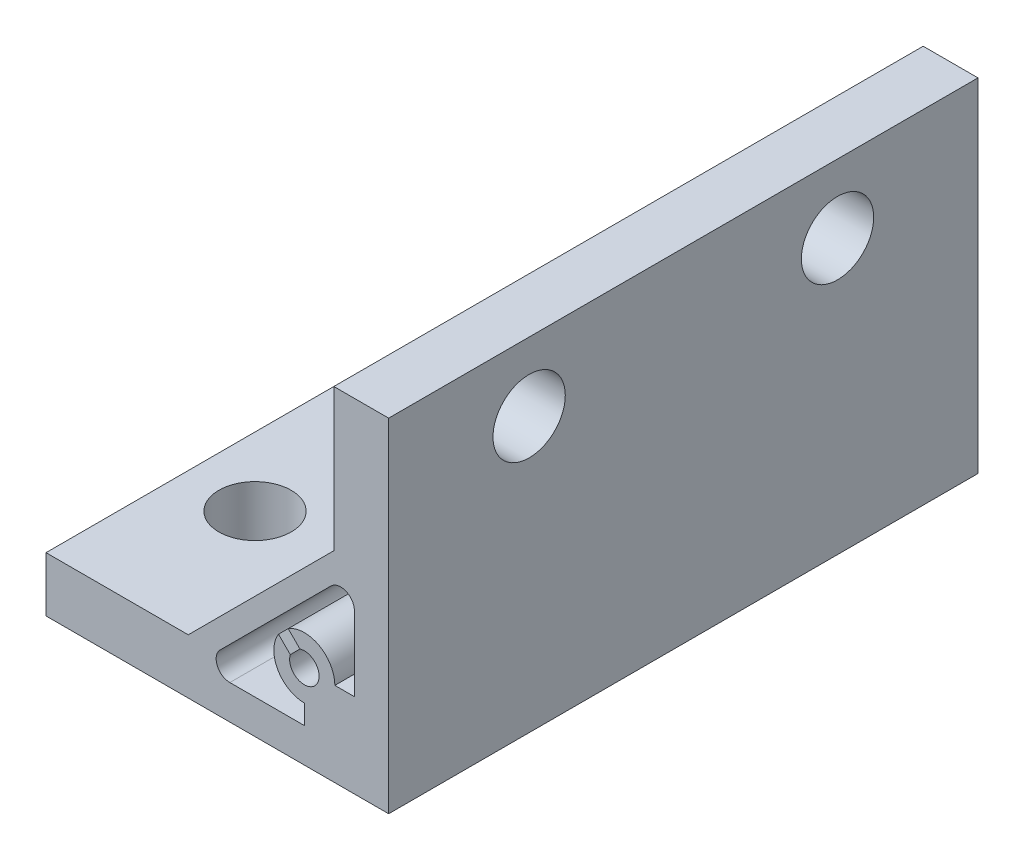
SolidWorks part; units mm, degrees
ref_plane "前视基准面" through (0, 0, 0) normal (0, 0, 1) x (1, 0, 0)
ref_plane "上视基准面" through (0, 0, 0) normal (0, 1, 0) x (1, 0, 0)
ref_plane "右视基准面" through (0, 0, 0) normal (1, 0, 0) x (0, 0, -1)
sketch "草图1" plane through (0, 0, 0) normal (0, 0, 1) x (1, 0, 0)
  line B0 (0, 0) -> (50, 0)
  line B1 (50, 0) -> (50, 50)
  line B2 (0, 8) -> (20.7574, 8)
  line B3 (42, 29.2426) -> (42, 50)
  line B4 (0, 8) -> (0, 0)
  line B5 (42, 50) -> (50, 50)
  line B6 (37.0613, 14.3529) -> (35.341, 16.0733)
  line B7 (35.6471, 12.9387) -> (33.9267, 14.659)
  line B8 (25.4142, 8.4142) -> (41.5858, 24.5858)
  line B9 (20.7574, 8) -> (42, 29.2426)
  line B10 (26.8284, 5) -> (37.7, 5)
  line B11 (45, 23.1716) -> (45, 12.3)
  line B12 (37.7, 5) -> (37.7, 7.85)
  line B13 (42.15, 12.3) -> (45, 12.3)
  arc B14 (33.9267, 14.659) -> (37.7, 7.85) centre (37.7, 12.3) ccw
  arc B15 (42.15, 12.3) -> (35.341, 16.0733) centre (37.7, 12.3) ccw
  arc B16 (35.6471, 12.9387) -> (37.0613, 14.3529) centre (37.7, 12.3) ccw
  arc B17 (25.4142, 8.4142) -> (26.8284, 5) centre (26.8284, 7) ccw
  arc B18 (45, 23.1716) -> (41.5858, 24.5858) centre (43, 23.1716) ccw
sketch_block_instance "A$C19004297-1"
sketch_block "A$C19004297"
extrude "凸台-拉伸1" add sketch "草图1" along normal mid plane 86
sketch "草图3" plane through (0, 8, 0) normal (0, 1, 0) x (1, 0, 0)
  line L0 (0, 0) -> (19.3601, 0) construction
  line L1 (0, -43) -> (0, 43) construction
  circle A0 centre (10, 22.5) radius 5.2767
  circle A1 centre (10, -22.5) radius 5.2767
  dimension "D1" = 22.5
  dimension "D2" = 10
extrude "切除-拉伸1" cut sketch "草图3" against normal through all
sketch "草图4" plane through (6.3787, -6.3787, 0) normal (-0.7071, 0.7071, 0) x (0, 0, 1)
  line L0 (43, 35.3553) -> (-43, 35.3553) construction
  line L1 (43, 50.3762) -> (43, 20.3345) construction
  line L2 (-43, 50.3762) -> (-43, 20.3345) construction
ref_plane "基准面2" through (25, 25, 0) normal (-0.7071, -0.7071, 0) x (0, 0, 1)
mirror "镜向1" about plane through (25, 25, 0) normal (-0.7071, -0.7071, 0) of "切除-拉伸1"
